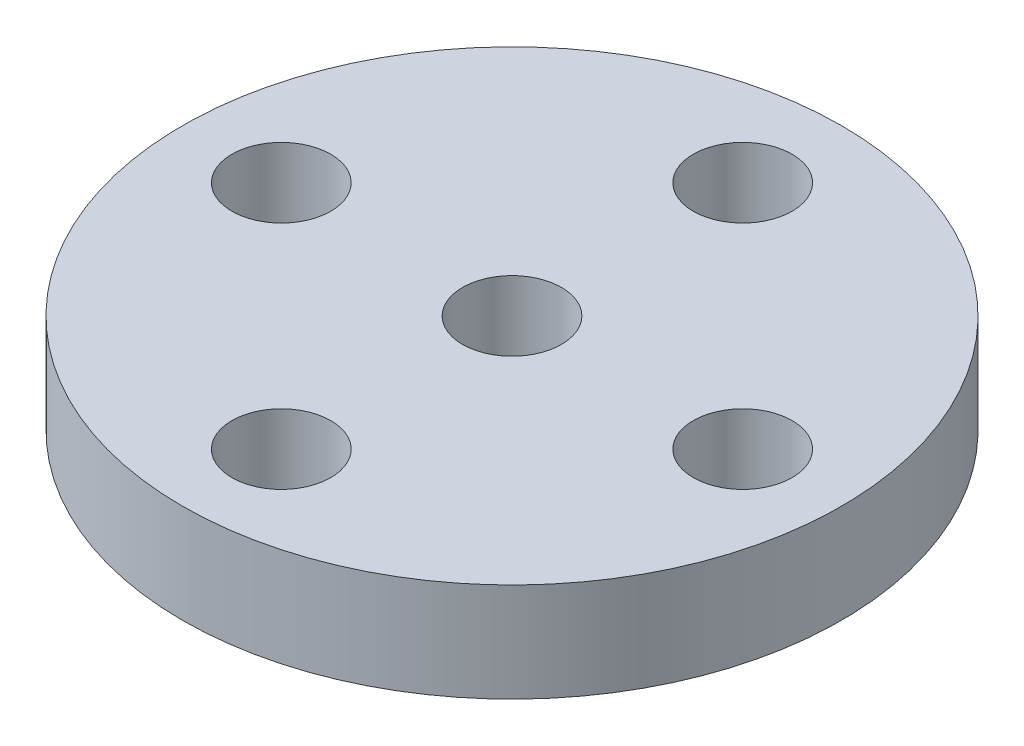
SolidWorks part; units mm, degrees
material "聚脂树脂"
ref_plane "前视基准面" through (0, 0, 0) normal (0, 0, 1) x (1, 0, 0)
ref_plane "上视基准面" through (0, 0, 0) normal (0, 1, 0) x (1, 0, 0)
ref_plane "右视基准面" through (0, 0, 0) normal (1, 0, 0) x (0, 0, -1)
other "Configuration Table"
sketch "草图1" plane through (0, 0, 0) normal (0, 1, 0) x (1, 0, 0)
  line L0 (0, 0) -> (0, 14.6276) construction
  line L1 (0, 0) -> (20.1674, 0) construction
  circle A0 centre (0, 0) radius 10
  circle A1 centre (0, 7) radius 1.5
  circle A2 centre (7, 0) radius 1.5
  circle A3 centre (0, 0) radius 1.5
  circle A4 centre (0, -7) radius 1.5
  circle A5 centre (-7, 0) radius 1.5
  dimension "D1" = 20
  dimension "D2" = 3
  dimension "D3" = 3
  dimension "D4" = 7
  dimension "D5" = 7
  dimension "D6" = 3
extrude "凸台-拉伸1" add sketch "草图1" along normal blind 3
